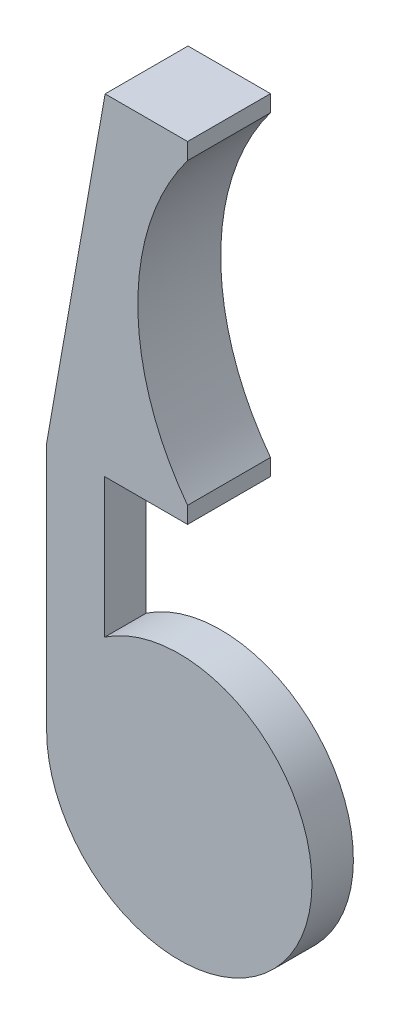
SolidWorks part; units mm, degrees
ref_plane "Front Plane" through (0, 0, 0) normal (0, 0, 1) x (1, 0, 0)
ref_plane "Top Plane" through (0, 0, 0) normal (0, 1, 0) x (1, 0, 0)
ref_plane "Right Plane" through (0, 0, 0) normal (1, 0, 0) x (0, 0, -1)
sketch "Sketch1" plane through (0, 0, 0) normal (0, 0, 1) x (1, 0, 0)
  circle A0 centre (0, 0) radius 20.32
  dimension "D1" = 40.64
extrude "Boss-Extrude1" add sketch "Sketch1" along normal blind 6.35
sketch "Sketch2" plane through (0, 0, 0) normal (0, 0, -1) x (-1, 0, 0)
  circle A0 centre (0, 0) radius 4.445
  circle A1 centre (0, 0) radius 3.175
  dimension "D1" = 8.89
  dimension "D2" = 6.35
extrude "Boss-Extrude2" add sketch "Sketch2" along normal blind 2.54
sketch "Sketch4" plane through (0, 0, 6.35) normal (0, 0, 1) x (1, 0, 0)
  line L1 (-11.43, 0) -> (-20.32, 0)
  line L2 (-11.43, 0) -> (-11.43, 38.1)
  line L3 (-11.43, 38.1) -> (-20.32, 38.1)
  line L4 (-20.32, 0) -> (-20.32, 38.1)
  circle A1 centre (0, 0) radius 20.32 construction
  point P4 (-23.5345, 0)
  dimension "D1" = 8.89
  dimension "D2" = 38.1
extrude "Boss-Extrude3" add sketch "Sketch4" against normal up to surface (6.35 mm away) up to face at (4.445, 0, 0)
sketch "Sketch5" plane through (0, 0, 6.35) normal (0, 0, 1) x (1, 0, 0)
  line L6 (-20.32, 38.1) -> (-11.3626, 88.9)
  line L7 (-11.3626, 88.9) -> (1.27, 88.9)
  line L8 (1.27, 88.9) -> (1.27, 86.36)
  line L9 (-20.32, 38.1) -> (-11.43, 38.1)
  line L10 (-11.43, 38.1) -> (1.27, 38.1)
  line L11 (1.27, 38.1) -> (1.27, 40.64)
  arc A1 (1.27, 40.64) -> (1.27, 86.36) centre (31.75, 63.5) cw
  dimension "D3" = 2.54
  dimension "D4" = 38.1
  dimension "D1" = 80
  dimension "D2" = 12.7
  dimension "D5" = 50.8
extrude "Boss-Extrude4" add sketch "Sketch5" against normal blind 12.7
